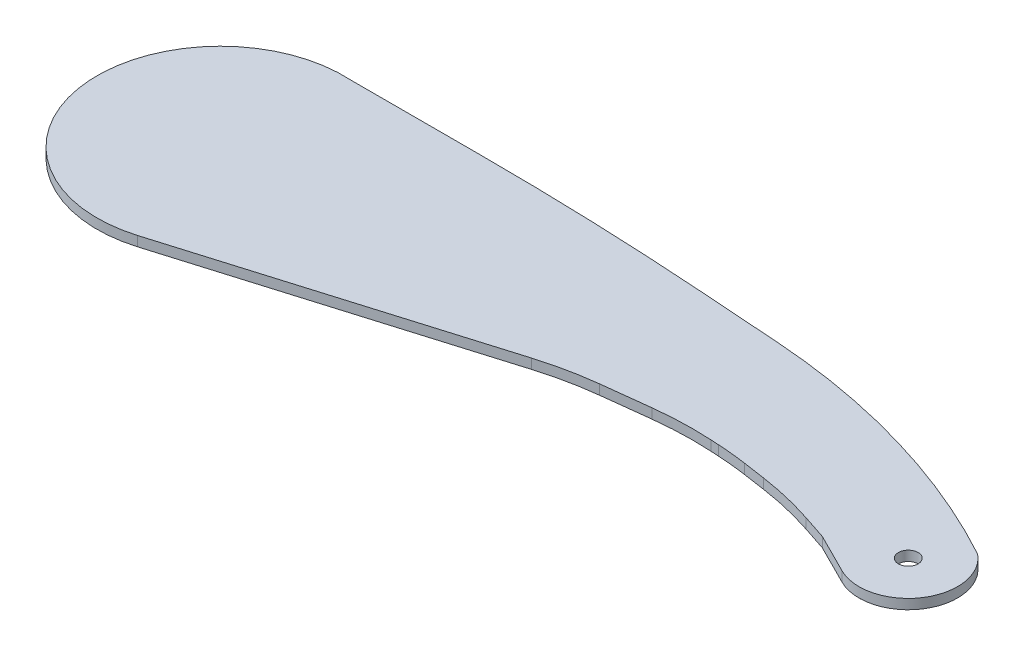
SolidWorks part; units mm, degrees
ref_plane "前视基准面" through (0, 0, 0) normal (0, 0, 1) x (1, 0, 0)
ref_plane "上视基准面" through (0, 0, 0) normal (0, 1, 0) x (1, 0, 0)
ref_plane "右视基准面" through (0, 0, 0) normal (1, 0, 0) x (0, 0, -1)
other "Configuration Table"
sketch "草图3" plane through (0, 0, 0) normal (0, 1, 0) x (1, 0, 0)
  line L0 (2.1711, 37.4371) -> (41.2504, 37.4371)
  line L1 (162.9536, -3.5906) -> (169.7662, -4.5868)
  line L2 (215.5007, 12.5897) -> (222.4375, 7.9108)
  line L3 (154.2747, -2.7061) -> (151.8624, -2.5662)
  line L4 (222.4375, 7.9108) -> (212.9675, -3.7218) construction
  line L5 (10.7641, -35.9219) -> (102.9648, -8.2939)
  line L6 (120.0349, -4.7647) -> (134.4387, -3.0775)
  line L7 (0, 0) -> (2.1711, 37.4371) construction
  line L8 (0, 0) -> (10.7641, -35.9219) construction
  line L9 (111.0068, 35.0011) -> (157.2243, 31.7693)
  line L10 (174.4409, 29.0425) -> (183.7736, 26.7156)
  line L11 (186.7285, -8.6025) -> (201.6213, -13.5333)
  line L12 (212.9675, -3.7218) -> (201.6213, -13.5333)
  line L13 (206.2343, -17.1257) -> (194.1749, -11.0679)
  circle A0 centre (0, 0) radius 37.5
  circle A1 centre (212.9675, -3.7218) radius 3
  circle A2 centre (212.9675, -3.7218) radius 15
  arc A3 (111.0068, 35.0011) -> (41.2504, 37.4371) centre (41.2504, -962.5629) ccw
  arc A4 (174.4409, 29.0425) -> (157.2243, 31.7693) centre (150.2487, -67.9871) ccw
  arc A5 (215.5007, 12.5897) -> (183.7736, 26.7156) centre (159.5814, -70.314) ccw
  arc A6 (102.9648, -8.2939) -> (120.0349, -4.7647) centre (131.6689, -104.0857) cw
  arc A7 (151.8624, -2.5662) -> (134.4387, -3.0775) centre (146.0727, -102.3985) ccw
  arc A8 (162.9536, -3.5906) -> (154.2747, -2.7061) centre (148.4851, -102.5384) ccw
  arc A9 (186.7285, -8.6025) -> (169.7662, -4.5868) centre (155.2977, -103.5346) ccw
  point P2 (76.1711, 37.4371)
  point P22 (165.9519, 31.159)
  point P25 (200.8825, 22.4498)
  point P28 (111.3455, -5.7826)
  point P31 (143.1282, -2.0597)
  point P34 (158.6335, -2.9589)
  point P37 (178.423, -5.8526)
  point P40 (0, 0)
  dimension "D1" = 75
  dimension "D20" = 30
  dimension "D21" = 6
  dimension "D22" = 1000
  dimension "D23" = 100
  dimension "D24" = 100
  dimension "D25" = 100
  dimension "D26" = 100
  dimension "D27" = 100
  dimension "D28" = 100
  dimension "D2" = 213
  dimension "D3" = 160
  dimension "D4" = 170
  dimension "D5" = 170
  dimension "D6" = 105
  dimension "D7" = 176
  dimension "D8" = 74
  dimension "D9" = 90
  dimension "D10" = 32
  dimension "D11" = 20
  dimension "D12" = 175
  dimension "D13" = 170
  dimension "D14" = 36
  dimension "D15" = 170
  dimension "D17" = 26
  dimension "D18" = 160
  dimension "D19" = 170
extrude "凸台-拉伸3" add sketch "草图3" along normal blind 3
sketch "草图4" plane through (0, 3, 0) normal (0, 1, 0) x (1, 0, 0)
  line L10 (194.1749, -11.0679) -> (206.2343, -17.1257)
  line L11 (222.4375, 7.9108) -> (215.5007, 12.5897)
  line L12 (183.7736, 26.7156) -> (174.4409, 29.0425)
  line L13 (157.2243, 31.7693) -> (111.0068, 35.0011)
  line L14 (41.2504, 37.4371) -> (2.1711, 37.4371)
  line L15 (10.7641, -35.9219) -> (102.9648, -8.2939)
  line L16 (120.0349, -4.7647) -> (134.4387, -3.0775)
  line L17 (151.8624, -2.5662) -> (154.2747, -2.7061)
  line L18 (162.9536, -3.5906) -> (169.7662, -4.5868)
  line L19 (186.7285, -8.6025) -> (194.1749, -11.0679)
  line L20 (194.1749, -11.0679) -> (206.2343, -17.1257)
  line L21 (222.4375, 7.9108) -> (215.5007, 12.5897)
  line L22 (183.7736, 26.7156) -> (174.4409, 29.0425)
  line L23 (157.2243, 31.7693) -> (111.0068, 35.0011)
  line L24 (41.2504, 37.4371) -> (2.1711, 37.4371)
  line L25 (10.7641, -35.9219) -> (102.9648, -8.2939)
  line L26 (120.0349, -4.7647) -> (134.4387, -3.0775)
  line L27 (151.8624, -2.5662) -> (154.2747, -2.7061)
  line L28 (162.9536, -3.5906) -> (169.7662, -4.5868)
  line L29 (186.7285, -8.6025) -> (194.1749, -11.0679)
  arc A0 (222.4375, 7.9108) -> (136.1596, 33.2423) centre (121.5107, -176.2462) ccw
  arc A9 (206.2343, -17.1257) -> (222.4375, 7.9108) centre (212.9675, -3.7218) ccw
  arc A10 (215.5007, 12.5897) -> (183.7736, 26.7156) centre (159.5814, -70.314) ccw
  arc A11 (174.4409, 29.0425) -> (157.2243, 31.7693) centre (150.2487, -67.9871) ccw
  arc A12 (111.0068, 35.0011) -> (41.2504, 37.4371) centre (41.2504, -962.5629) ccw
  arc A13 (2.1711, 37.4371) -> (10.7641, -35.9219) centre (0, 0) ccw
  arc A14 (120.0349, -4.7647) -> (102.9648, -8.2939) centre (131.6689, -104.0857) ccw
  arc A15 (151.8624, -2.5662) -> (134.4387, -3.0775) centre (146.0727, -102.3985) ccw
  arc A16 (162.9536, -3.5906) -> (154.2747, -2.7061) centre (148.4851, -102.5384) ccw
  arc A17 (186.7285, -8.6025) -> (169.7662, -4.5868) centre (155.2977, -103.5346) ccw
  arc A18 (206.2343, -17.1257) -> (222.4375, 7.9108) centre (212.9675, -3.7218) ccw
  arc A19 (215.5007, 12.5897) -> (183.7736, 26.7156) centre (159.5814, -70.314) ccw
  arc A20 (174.4409, 29.0425) -> (157.2243, 31.7693) centre (150.2487, -67.9871) ccw
  arc A21 (111.0068, 35.0011) -> (41.2504, 37.4371) centre (41.2504, -962.5629) ccw
  arc A22 (2.1711, 37.4371) -> (10.7641, -35.9219) centre (0, 0) ccw
  arc A23 (120.0349, -4.7647) -> (102.9648, -8.2939) centre (131.6689, -104.0857) ccw
  arc A24 (151.8624, -2.5662) -> (134.4387, -3.0775) centre (146.0727, -102.3985) ccw
  arc A25 (162.9536, -3.5906) -> (154.2747, -2.7061) centre (148.4851, -102.5384) ccw
  arc A26 (186.7285, -8.6025) -> (169.7662, -4.5868) centre (155.2977, -103.5346) ccw
  point P4 (222.4375, 7.9108)
  point P12 (137.0727, 33.1784)
  point P17 (222.4375, 7.9108)
  point P22 (0, 0)
  point P27 (0, 0)
  line M22 (222.4375, 7.9108) -> (215.5007, 12.5897)
  arc M23 (215.5007, 12.5897) -> (183.7736, 26.7156) centre (159.5814, -70.314) ccw
  line M24 (183.7736, 26.7156) -> (174.4409, 29.0425)
  arc M25 (174.4409, 29.0425) -> (157.2243, 31.7693) centre (150.2487, -67.9871) ccw
  line M26 (157.2243, 31.7693) -> (111.0068, 35.0011)
  dimension "D2" = 210
  dimension "D1" = 0
extrude "切除-拉伸1" cut sketch "草图4" against normal through all contours A0 M22 M23 M24 M25 M26
sketch "草图5" plane through (0, 3, 0) normal (0, 1, 0) x (1, 0, 0)
  line L0 (0, 37.5) -> (80, 37.5)
  line L1 (212.9675, -3.7218) -> (206.2343, -17.1257)
  line L2 (10.7641, -35.9219) -> (100.8012, -8.9161)
  line L3 (194.1749, -11.0679) -> (186.9293, -8.898)
  line L4 (222.4375, 7.9108) -> (212.9675, -3.7218)
  line L5 (0, 0) -> (10.7641, -35.9219)
  line L6 (0, 0) -> (0, 37.5)
  line L8 (136.1596, 33.2423) -> (111.0068, 35.0011)
  line L9 (41.2504, 37.4371) -> (2.1711, 37.4371)
  line L10 (10.7641, -35.9219) -> (102.9648, -8.2939)
  line L11 (120.0349, -4.7647) -> (134.4387, -3.0775)
  line L12 (151.8624, -2.5662) -> (154.2747, -2.7061)
  line L13 (162.9536, -3.5906) -> (169.7662, -4.5868)
  line L14 (186.7285, -8.6025) -> (194.1749, -11.0679)
  line L15 (194.1749, -11.0679) -> (206.2343, -17.1257)
  line L16 (136.1596, 33.2423) -> (111.0068, 35.0011) construction
  line L17 (41.2504, 37.4371) -> (2.1711, 37.4371) construction
  line L18 (10.7641, -35.9219) -> (102.9648, -8.2939) construction
  line L19 (120.0349, -4.7647) -> (134.4387, -3.0775) construction
  line L20 (151.8624, -2.5662) -> (154.2747, -2.7061) construction
  line L21 (162.9536, -3.5906) -> (169.7662, -4.5868) construction
  line L22 (186.7285, -8.6025) -> (194.1749, -11.0679) construction
  line L23 (194.1749, -11.0679) -> (206.2343, -17.1257) construction
  circle A0 centre (0, 0) radius 37.5
  arc A1 (80, 37.5) -> (175.7001, 25.8832) centre (80, -362.5) cw
  arc A2 (186.9293, -8.898) -> (100.8012, -8.9161) centre (143.8956, -152.5924) ccw
  arc A3 (175.7001, 25.8832) -> (222.4375, 7.9108) centre (127.8501, -168.3084) cw
  arc A8 (206.2343, -17.1257) -> (222.4375, 7.9108) centre (212.9675, -3.7218) ccw
  arc A9 (222.4375, 7.9108) -> (136.1596, 33.2423) centre (121.5107, -176.2462) ccw
  arc A10 (111.0068, 35.0011) -> (41.2504, 37.4371) centre (41.2504, -962.5629) ccw
  arc A11 (2.1711, 37.4371) -> (10.7641, -35.9219) centre (0, 0) ccw
  arc A12 (120.0349, -4.7647) -> (102.9648, -8.2939) centre (131.6689, -104.0857) ccw
  arc A13 (151.8624, -2.5662) -> (134.4387, -3.0775) centre (146.0727, -102.3985) ccw
  arc A14 (162.9536, -3.5906) -> (154.2747, -2.7061) centre (148.4851, -102.5384) ccw
  arc A15 (186.7285, -8.6025) -> (169.7662, -4.5868) centre (155.2977, -103.5346) ccw
  arc A16 (206.2343, -17.1257) -> (222.4375, 7.9108) centre (212.9675, -3.7218) ccw construction
  arc A18 (111.0068, 35.0011) -> (41.2504, 37.4371) centre (41.2504, -962.5629) ccw construction
  arc A19 (2.1711, 37.4371) -> (10.7641, -35.9219) centre (0, 0) ccw construction
  arc A20 (120.0349, -4.7647) -> (102.9648, -8.2939) centre (131.6689, -104.0857) ccw construction
  arc A21 (151.8624, -2.5662) -> (134.4387, -3.0775) centre (146.0727, -102.3985) ccw construction
  arc A22 (162.9536, -3.5906) -> (154.2747, -2.7061) centre (148.4851, -102.5384) ccw construction
  arc A23 (186.7285, -8.6025) -> (169.7662, -4.5868) centre (155.2977, -103.5346) ccw construction
  dimension "D2" = 400
  dimension "D4" = 150
  dimension "D5" = 80
  dimension "D7" = 200
  dimension "D3" = 170
  dimension "D6" = 94
  dimension "D1" = 0
